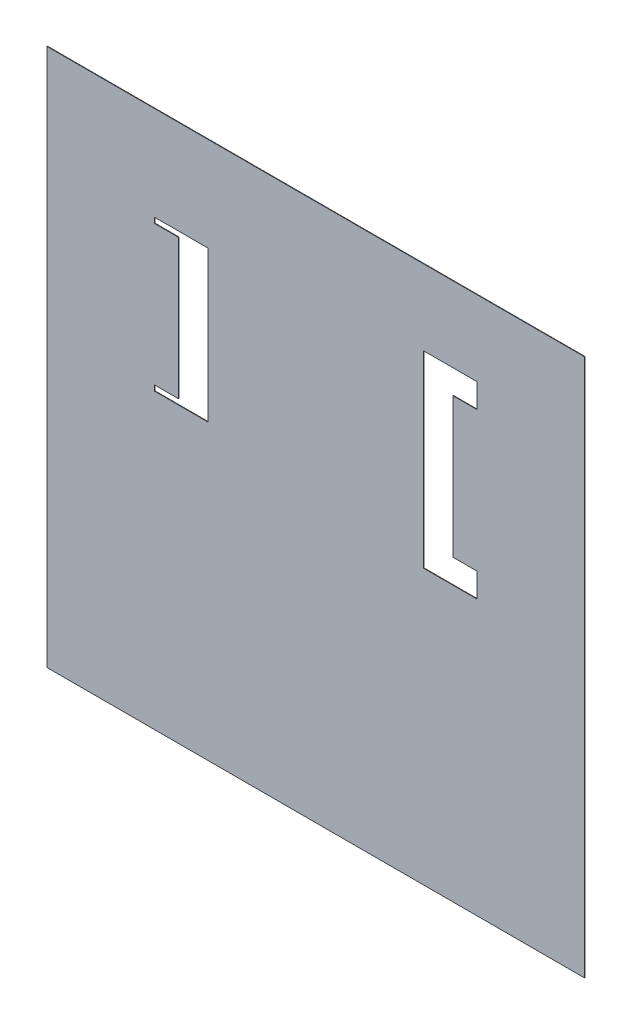
SolidWorks part; units mm, degrees
material "Aluminum Bronze"
ref_plane "Front Plane" through (0, 0, 0) normal (0, 0, 1) x (1, 0, 0)
ref_plane "Top Plane" through (0, 0, 0) normal (0, 1, 0) x (1, 0, 0)
ref_plane "Right Plane" through (0, 0, 0) normal (1, 0, 0) x (0, 0, -1)
sketch "Sketch1" plane through (0, 0, 0) normal (0, 0, 1) x (1, 0, 0)
  line L1 (0, 0) -> (25.4, 0)
  line L2 (0, 0) -> (0, 25.4)
  line L3 (0, 25.4) -> (25.4, 25.4)
  line L4 (25.4, 0) -> (25.4, 25.4)
  dimension "D1" = 25.4
  dimension "D2" = 25.4
extrude "Boss-Extrude1" add sketch "Sketch1" along normal blind 0.0254
sketch "Sketch4" plane through (0, 0, 0.0254) normal (0, 0, 1) x (1, 0, 0)
  line L0 (25.4, 25.4) -> (0, 25.4) construction
  line L1 (5.08, 20.955) -> (7.62, 20.955)
  line L2 (5.08, 20.955) -> (5.08, 20.701)
  line L3 (5.08, 13.843) -> (7.62, 13.843)
  line L4 (7.62, 20.955) -> (7.62, 13.843)
  line L5 (17.78, 21.844) -> (20.32, 21.844)
  line L6 (17.78, 21.844) -> (17.78, 12.954)
  line L7 (17.78, 12.954) -> (20.32, 12.954)
  line L8 (20.32, 21.844) -> (20.32, 20.701)
  line L9 (5.08, 14.097) -> (5.08, 13.843)
  line L10 (5.08, 14.097) -> (6.223, 14.097)
  line L11 (20.32, 14.097) -> (20.32, 12.954)
  line L12 (5.08, 20.701) -> (6.223, 20.701)
  line L13 (6.223, 14.097) -> (6.223, 20.701)
  line L14 (20.32, 14.097) -> (19.177, 14.097)
  line L16 (20.32, 20.701) -> (19.177, 20.701)
  line L17 (19.177, 14.097) -> (19.177, 20.701)
  point P8 (6.35, 13.843)
  point P9 (19.05, 12.954)
  point P10 (6.35, 20.955)
  point P13 (12.7, 25.4)
  point P22 (6.223, 17.399)
  point P23 (7.62, 17.399)
  point P24 (19.177, 17.399)
  point P25 (17.78, 17.399)
  dimension "D1" = 2.54
  dimension "D2" = 2.54
  dimension "D3" = 12.7
  dimension "D4" = 6.35
  dimension "D5" = 8.89
  dimension "D6" = 7.112
  dimension "D7" = 3.556
  dimension "D8" = 4.445
  dimension "D9" = 6.604
  dimension "D10" = 0
  dimension "D11" = 1.143
  dimension "D12" = 6.604
  dimension "D13" = 0
  dimension "D14" = 1.143
extrude "Cut-Extrude1" cut sketch "Sketch4" against normal through all
